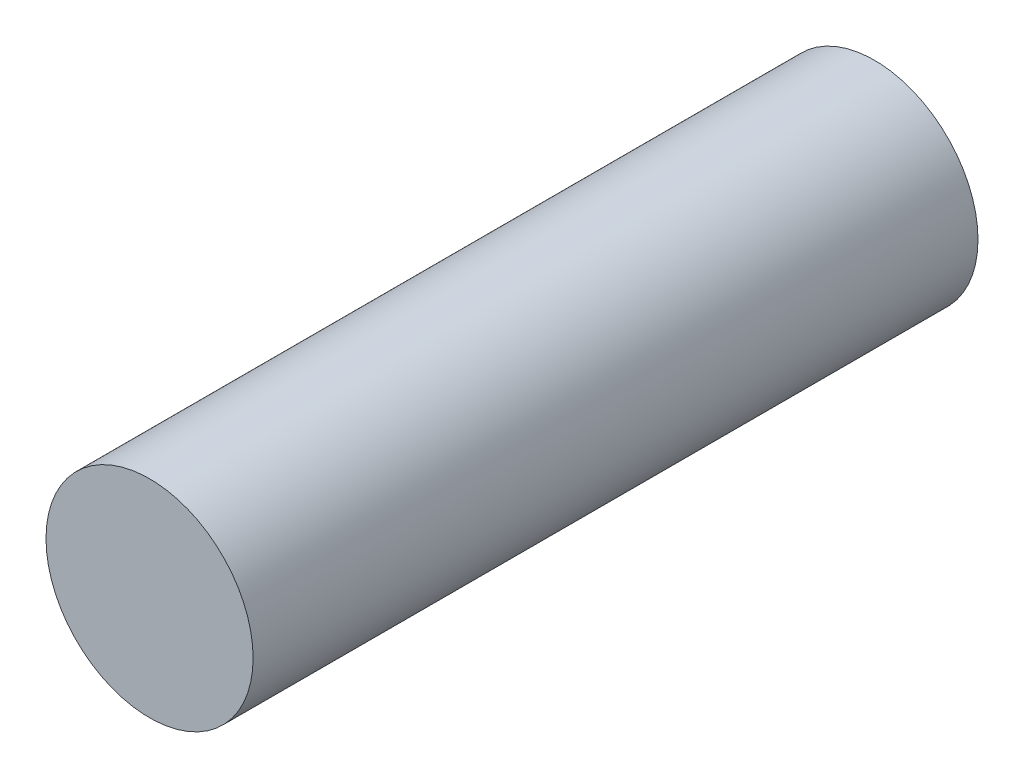
SolidWorks part; units mm, degrees
ref_plane "Front Plane" through (0, 0, 0) normal (0, 0, 1) x (1, 0, 0)
ref_plane "Top Plane" through (0, 0, 0) normal (0, 1, 0) x (1, 0, 0)
ref_plane "Right Plane" through (0, 0, 0) normal (1, 0, 0) x (0, 0, -1)
sketch "Sketch1" plane through (0, 0, 0) normal (0, 0, 1) x (1, 0, 0)
  circle A0 centre (0, 0) radius 38.1
  dimension "D1" = 76.2
extrude "Boss-Extrude1" add sketch "Sketch1" along normal mid plane 266.7
